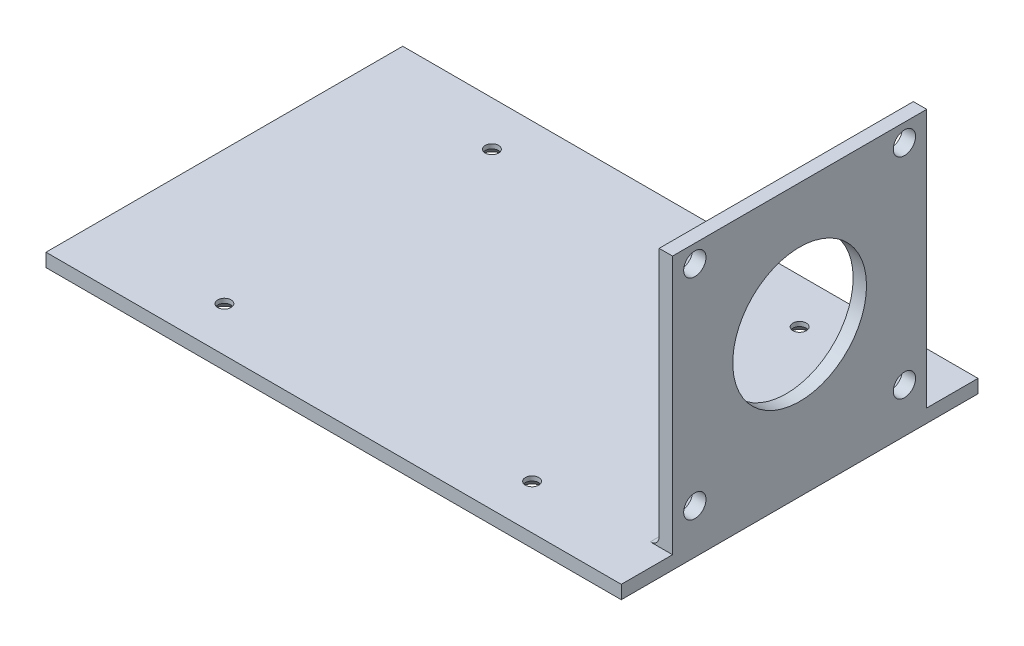
SolidWorks part; units mm, degrees
material "1060 Alloy"
ref_plane "Front Plane" through (0, 0, 0) normal (0, 0, 1) x (1, 0, 0)
ref_plane "Top Plane" through (0, 0, 0) normal (0, 1, 0) x (1, 0, 0)
ref_plane "Right Plane" through (0, 0, 0) normal (1, 0, 0) x (0, 0, -1)
sketch "Sketch1" plane through (0, 0, 0) normal (0, 1, 0) x (1, 0, 0)
  line L0 (129, 80) -> (129, 70) construction
  line L1 (0, 0) -> (129, 0)
  line L2 (0, 0) -> (0, 80)
  line L3 (0, 80) -> (129, 80)
  line L4 (129, 0) -> (129, 80)
  line L5 (129, 70) -> (-1.8165, 70) construction
  line L6 (129, 40) -> (-13.8582, 40) construction
  circle A0 centre (99, 70) radius 1.5
  circle A1 centre (30, 70) radius 1.5
  circle A2 centre (99, 10) radius 1.5
  circle A3 centre (30, 10) radius 1.5
  dimension "D6" = 3
  dimension "D7" = 3
  dimension "D1" = 129
  dimension "D2" = 80
  dimension "D3" = 10
  dimension "D4" = 30
  dimension "D5" = 30
  dimension "D8" = 80
extrude "Boss-Extrude1" add sketch "Sketch1" along normal blind 3
sketch "Sketch2" plane through (0, 3, 0) normal (0, 1, 0) x (1, 0, 0)
  line L5 (129, 40) -> (129, 68.5) construction
  line L6 (129, 68.5) -> (129, 11.5)
  line L7 (129, 68.5) -> (126, 68.5)
  line L8 (126, 68.5) -> (126, 11.5)
  line L9 (126, 11.5) -> (129, 11.5)
  dimension "D2" = 28.5
  dimension "D3" = 28.5
extrude "Boss-Extrude2" add sketch "Sketch2" along normal blind 58
fillet "Fillet1" radius 2 1 edges at (126, 3, -40)
sketch "Sketch3" plane through (129, 0, 0) normal (1, 0, 0) x (0, 0, -1)
  line L2 (67.5, 61) -> (63.5, 61) construction
  line L3 (67.5, 6) -> (12.5, 6)
  line L4 (67.5, 6) -> (67.5, 61)
  line L7 (40, 33.5) -> (29.966, 33.5) construction
  line L9 (63.5, 61) -> (63.5, 57) construction
  circle A0 centre (63.5, 57) radius 2.5
  circle A1 centre (16.5, 57) radius 2.5
  circle A2 centre (16.5, 10) radius 2.5
  circle A3 centre (63.5, 10) radius 2.5
  circle A4 centre (40, 33.5) radius 15
  dimension "D6" = 5
  dimension "D7" = 30
  dimension "D4" = 4
  dimension "D5" = 4
extrude "Cut-Extrude1" cut sketch "Sketch3" against normal through all contours A1 | A4 | A0 | A2 | A3
chamfer "Chamfer3" distance 2 angle 45 4 edges at (30, 0, -11.5) (30, 0, -68.5) (99, 0, -68.5) (99, 0, -11.5)
